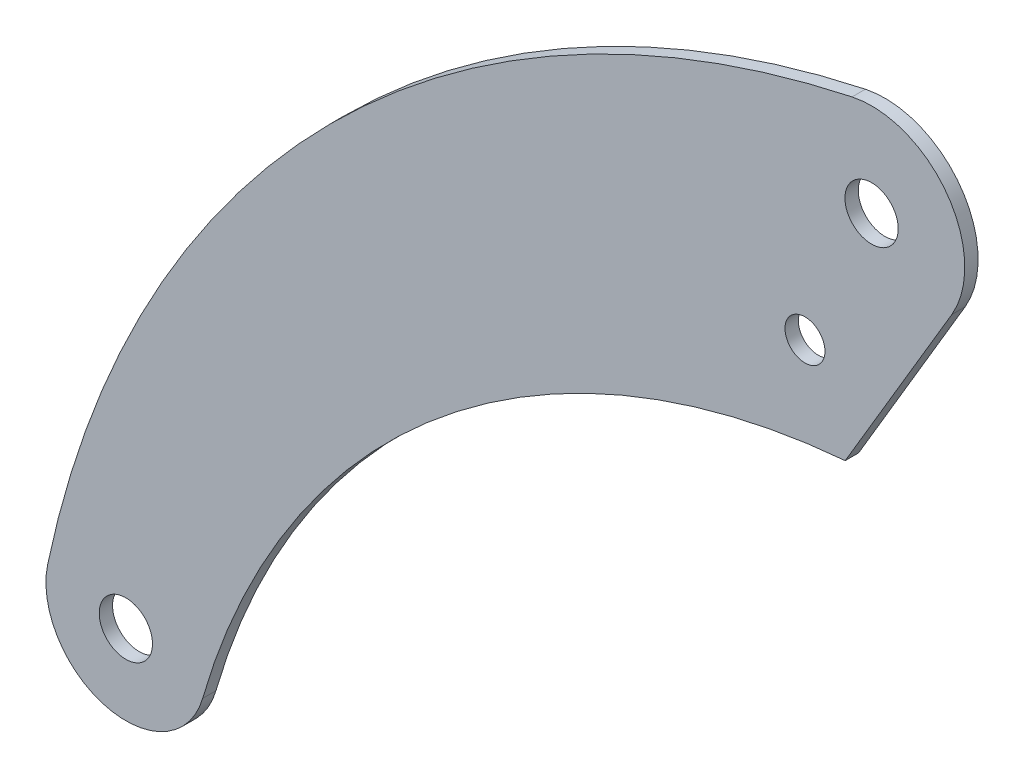
SolidWorks part; units mm, degrees
ref_plane "Front Plane" through (0, 0, 0) normal (0, 0, 1) x (1, 0, 0)
ref_plane "Top Plane" through (0, 0, 0) normal (0, 1, 0) x (1, 0, 0)
ref_plane "Right Plane" through (0, 0, 0) normal (1, 0, 0) x (0, 0, -1)
sketch "Sketch1" plane through (0, 0, 0) normal (0, 0, 1) x (1, 0, 0)
  line L0 (60.2204, -35.6862) -> (-19.7796, -170.6862)
  circle A0 centre (0, 0) radius 20
  circle A1 centre (-50, -107.2668) radius 15
  circle A2 centre (-560, -550) radius 20
  arc A3 (-502.3419, -566.5995) -> (-618.7157, -537.6524) centre (-560, -550) cw
  arc A4 (60.2204, -35.6862) -> (-14.6346, 68.4531) centre (0, 0) ccw
  arc A5 (-19.7796, -170.6862) -> (-502.3419, -566.5995) centre (26.1907, -718.7616) ccw
  arc A6 (-14.6346, 68.4531) -> (-618.7157, -537.6524) centre (149.4818, -699.1997) ccw
  dimension "D1" = 40
  dimension "D2" = 30
  dimension "D3" = 40
  dimension "D8" = 60
  dimension "D9" = 70
  dimension "D12" = 550
  dimension "D13" = 785
  dimension "D4" = 50
  dimension "D5" = 107.2668
  dimension "D6" = 560
  dimension "D7" = 550
  dimension "D10" = 135
  dimension "D11" = 80
extrude "Boss-Extrude1" add sketch "Sketch1" along normal mid plane 10
